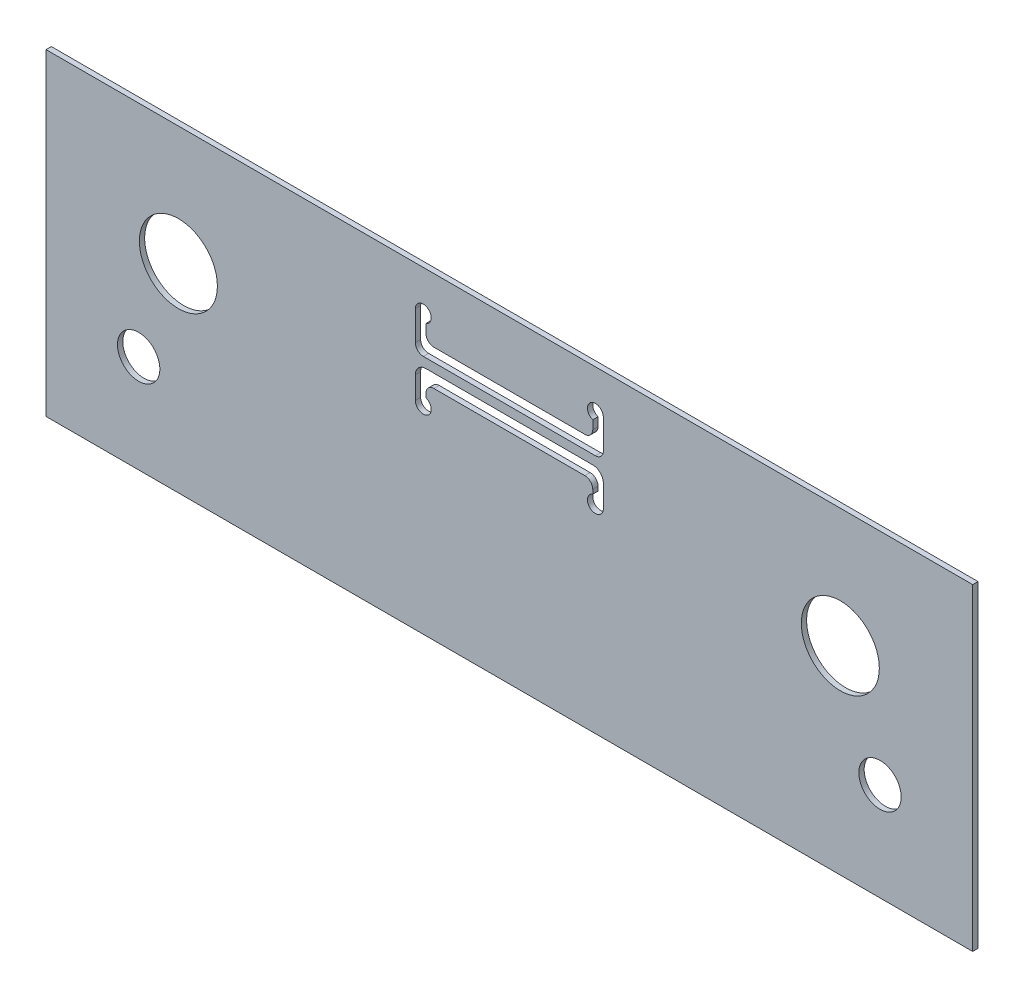
SolidWorks part; units mm, degrees
ref_plane "Front Plane" through (0, 0, 0) normal (0, 0, 1) x (1, 0, 0)
ref_plane "Top Plane" through (0, 0, 0) normal (0, 1, 0) x (1, 0, 0)
ref_plane "Right Plane" through (0, 0, 0) normal (1, 0, 0) x (0, 0, -1)
sketch "Sketch1" plane through (0, 0, 0) normal (0, 0, 1) x (1, 0, 0)
  line L0 (0, 0) -> (35, 0)
  line L1 (35, 0) -> (35, -12)
  line L2 (35, -12) -> (0, -12)
  line L3 (0, -12) -> (0, 0)
  line L4 (13.95, -4.5) -> (13.95, -3.66)
  line L5 (17.5, 4.0959) -> (17.5, -15.1104) construction
  line L6 (14.35, -2.11) -> (14.35, -1.7828)
  line L7 (14.65, -2.41) -> (20.35, -2.41)
  line L8 (20.65, -2.11) -> (20.65, -1.7828)
  line L9 (13.95, -1.5) -> (13.95, -2.61)
  line L10 (14.25, -2.91) -> (20.75, -2.91)
  line L11 (21.05, -2.61) -> (21.05, -1.5)
  line L12 (17.5, -2.41) -> (17.5, -2.91) construction
  line L13 (17.5, -2.41) -> (17.5, -2.91) construction
  line L14 (14.35, -3.26) -> (20.65, -3.26)
  line L15 (21.05, -3.66) -> (21.05, -4.5)
  line L16 (14.35, -4.2172) -> (14.35, -4.06)
  line L17 (14.65, -3.76) -> (20.35, -3.76)
  line L18 (20.65, -4.06) -> (20.65, -4.2172)
  line L19 (17.5, -3.26) -> (17.5, -3.76) construction
  line L20 (17.5, -3.76) -> (17.5, -3.26) construction
  circle A0 centre (3.5, -8.3) radius 0.8001
  circle A1 centre (5, -4.5) radius 1.4732
  arc A2 (14.35, -1.7828) -> (13.95, -1.5) centre (14.25, -1.5) ccw
  arc A3 (21.05, -1.5) -> (20.65, -1.7828) centre (20.75, -1.5) ccw
  arc A4 (20.65, -4.2172) -> (21.05, -4.5) centre (20.75, -4.5) ccw
  arc A5 (13.95, -4.5) -> (14.35, -4.2172) centre (14.25, -4.5) ccw
  circle A6 centre (30, -4.5) radius 1.4732
  circle A7 centre (31.5, -8.3) radius 0.8001
  arc A8 (14.65, -2.41) -> (14.35, -2.11) centre (14.65, -2.11) cw
  arc A9 (20.35, -2.41) -> (20.65, -2.11) centre (20.35, -2.11) ccw
  arc A10 (13.95, -2.61) -> (14.25, -2.91) centre (14.25, -2.61) ccw
  arc A11 (20.75, -2.91) -> (21.05, -2.61) centre (20.75, -2.61) ccw
  arc A12 (13.95, -3.66) -> (14.35, -3.26) centre (14.35, -3.66) cw
  arc A13 (20.65, -3.26) -> (21.05, -3.66) centre (20.65, -3.66) cw
  arc A14 (14.35, -4.06) -> (14.65, -3.76) centre (14.65, -4.06) cw
  arc A15 (20.35, -3.76) -> (20.65, -4.06) centre (20.35, -4.06) cw
  point P14 (17.5, 0)
  point P47 (17.5, -2.66)
  dimension "D5" = 6.5
  dimension "D13" = 3
  dimension "D18" = 4.5
  dimension "D25" = 0.3
  dimension "D32" = 1.6002
  dimension "D34" = 2.9464
  dimension "D10" = 0.4
  dimension "D14" = 1.5
  dimension "D20" = 14.25
  dimension "D12" = 0.5
  dimension "D15" = 0.3
  dimension "D11" = 0.3
  dimension "D9" = 0.3
  dimension "D1" = 35
  dimension "D2" = 12
  dimension "D4" = 3.5
  dimension "D6" = 3.5
  dimension "D7" = 0.4
  dimension "D8" = 2.91
  dimension "D16" = 8.3
  dimension "D17" = 5
  dimension "D19" = 0.4
  dimension "D21" = 5
  dimension "D22" = 0.5
  dimension "D23" = 0.35
  dimension "D24" = 0.4
extrude "Boss-Extrude1" add sketch "Sketch1" along normal blind 0.2
